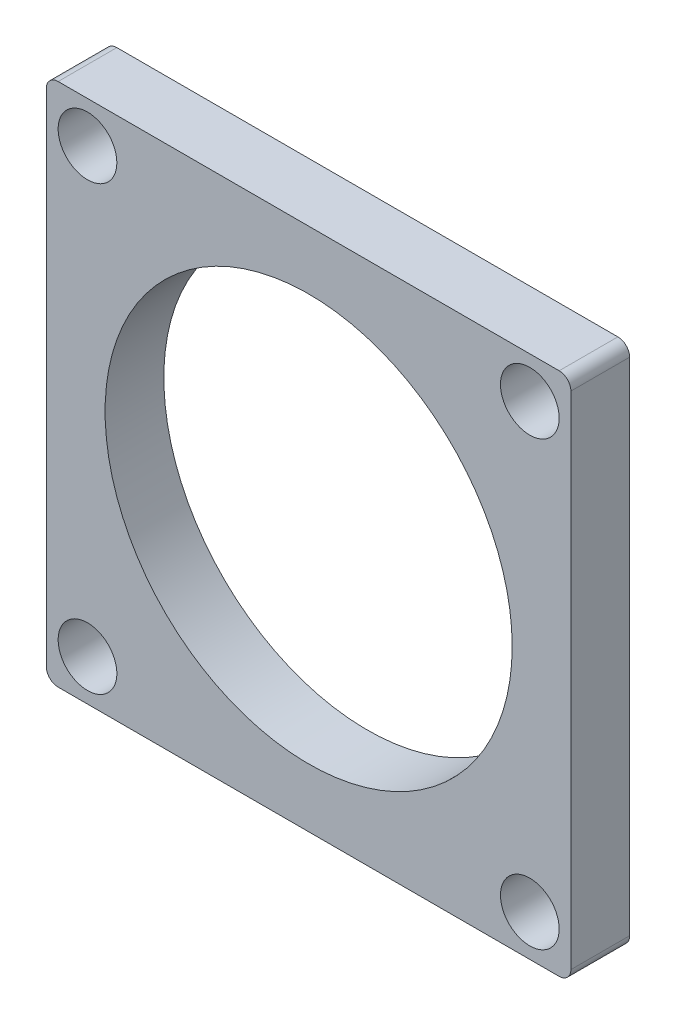
SolidWorks part; units mm, degrees
ref_plane "Alzado" through (0, 0, 0) normal (0, 0, 1) x (1, 0, 0)
ref_plane "Planta" through (0, 0, 0) normal (0, 1, 0) x (1, 0, 0)
ref_plane "Vista lateral" through (0, 0, 0) normal (1, 0, 0) x (0, 0, -1)
sketch "Croquis1" plane through (0, 0, 0) normal (0, 0, 1) x (1, 0, 0)
  line L0 (0, 0) -> (-34.67, 0) construction
  line L1 (0, 0) -> (0, 58.4687) construction
  line L3 (-44.67, -44.67) -> (-44.67, 44.67)
  line L4 (-44.67, 44.67) -> (44.67, 44.67)
  line L7 (44.67, -44.67) -> (44.67, 44.67)
  line L8 (-44.67, -44.67) -> (44.67, -44.67)
  point P11 (0, 44.67)
extrude "Saliente-Extruir2" add sketch "Croquis1" along normal blind 10 contours L7 L4 L3 L8
sketch "Croquis3" plane through (0, 0, 10) normal (0, 0, 1) x (1, 0, 0)
  circle A0 centre (0, 0) radius 34.67
  dimension "D1" = 69.34
extrude "Cortar-Extruir2" cut sketch "Croquis3" against normal blind 10 contours A0
sketch "Croquis4" plane through (0, 0, 10) normal (0, 0, 1) x (1, 0, 0)
  line L0 (0, 0) -> (0, -59.5572) construction
  line L1 (0, 0) -> (55.0065, 0) construction
  line L2 (-44.67, -44.67) -> (44.67, -44.67) construction
  line L3 (44.67, -44.67) -> (44.67, 44.67) construction
  circle A0 centre (37.67, -37.67) radius 5
  circle A1 centre (-37.67, -37.67) radius 5
  circle A2 centre (-37.67, 37.67) radius 5
  circle A3 centre (37.67, 37.67) radius 5
  dimension "D1" = 10
  dimension "D2" = 7
  dimension "D3" = 7
extrude "Cortar-Extruir3" cut sketch "Croquis4" against normal blind 10
fillet "Redondeo2" radius 2 4 edges at (-44.67, 44.67, 5) (-44.67, -44.67, 5) (44.67, -44.67, 5) (44.67, 44.67, 5)
